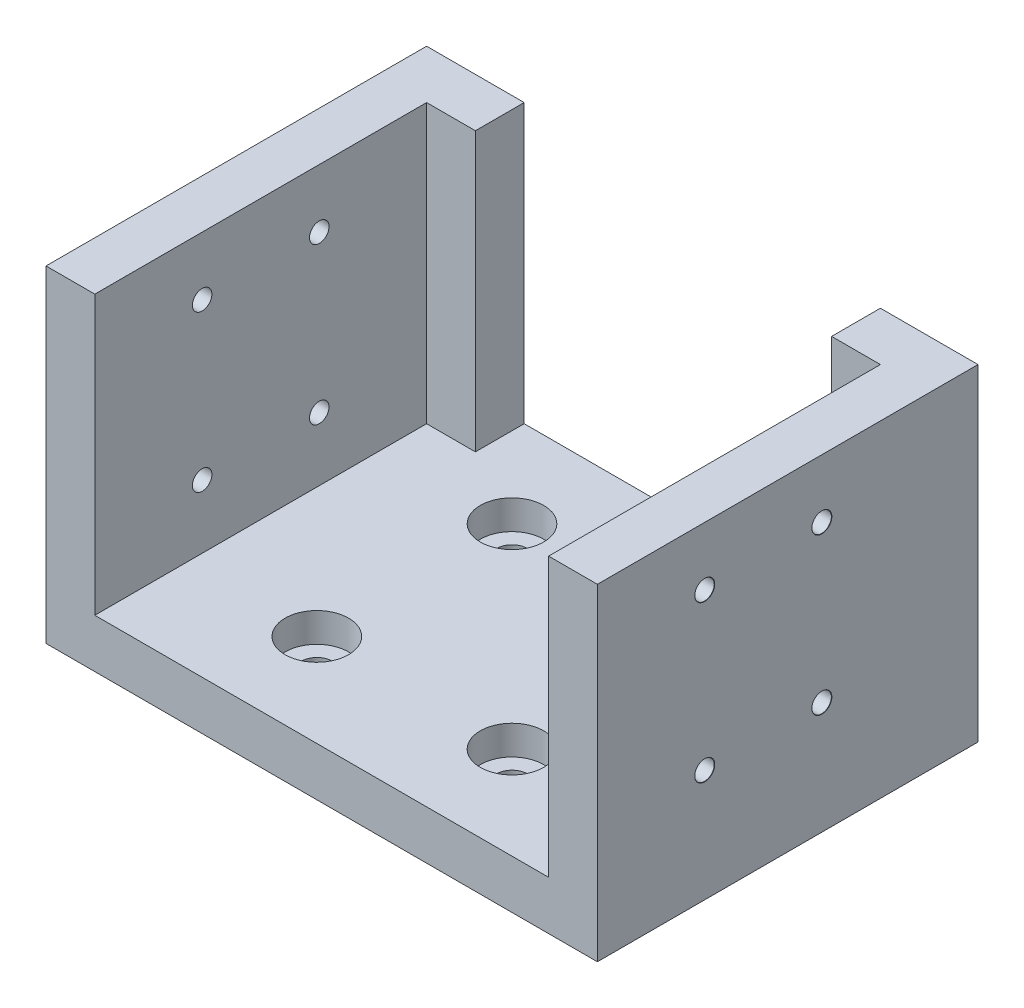
SolidWorks part; units mm, degrees
material "ABS"
ref_plane "Front Plane" through (0, 0, 0) normal (0, 0, 1) x (1, 0, 0)
ref_plane "Top Plane" through (0, 0, 0) normal (0, 1, 0) x (1, 0, 0)
ref_plane "Right Plane" through (0, 0, 0) normal (1, 0, 0) x (0, 0, -1)
sketch "Sketch9" plane through (0, 0, 0) normal (0, 1, 0) x (1, 0, 0)
  line L1 (-28.25, -19.5) -> (28.25, -19.5)
  line L2 (-28.25, -19.5) -> (-28.25, 19.5)
  line L3 (-28.25, 19.5) -> (28.25, 19.5)
  line L4 (28.25, -19.5) -> (28.25, 19.5)
  line L5 (-28.25, -19.5) -> (28.25, 19.5) construction
  line L6 (-28.25, 19.5) -> (28.25, -19.5) construction
  point P0 (0, 0)
  dimension "D1" = 56.5
  dimension "D2" = 39
extrude "Boss-Extrude7" add sketch "Sketch9" along normal blind 33.5 contours L2 L1 L4 L3
sketch "Sketch10" plane through (28.25, 0, 0) normal (1, 0, 0) x (0, 0, -1)
  line L0 (-2.5, 33.5) -> (-2.5, 0) construction
  line L2 (-19.5, 19.5) -> (19.5, 19.5) construction
  line L3 (-19.5, 33.5) -> (-19.5, 0) construction
  line L4 (19.5, 33.5) -> (19.5, 0) construction
  line L5 (-19.5, 0) -> (19.5, 0) construction
  line L6 (-19.5, 33.5) -> (19.5, 33.5) construction
  circle A0 centre (-8.5, 11.5) radius 1.05
  circle A1 centre (3.5, 11.5) radius 1.05
  circle A2 centre (3.5, 27.5) radius 1.05
  circle A3 centre (-8.5, 27.5) radius 1.05
  point P13 (-8.5, 11.5)
  point P15 (3.5, 11.5)
  point P17 (3.5, 27.5)
  point P19 (-8.5, 27.5)
  dimension "D2" = 8
  dimension "D1" = 19.5
  dimension "D3" = 22
  dimension "D4" = 6
  dimension "D5" = 6
  dimension "D6" = 16
sketch "Sketch11" plane through (0, 33.5, 0) normal (0, 1, 0) x (1, 0, 0)
  line L4 (-28.25, -19.5) -> (28.25, -19.5) construction
  line L6 (-23.25, -14.5) -> (-23.25, -19.5)
  line L7 (-23.25, -19.5) -> (23.25, -19.5)
  line L8 (23.25, 14.5) -> (-23.25, 14.5)
  line L9 (-23.25, 14.5) -> (-23.25, -14.5)
  line L10 (-23.25, -14.5) -> (23.25, -14.5)
  line L11 (23.25, -14.5) -> (23.25, 14.5)
  line L12 (23.25, 14.5) -> (-23.25, 14.5)
  line L13 (-23.25, 14.5) -> (-23.25, -14.5)
  line L15 (23.25, -14.5) -> (23.25, 14.5)
  line L16 (23.25, -14.5) -> (23.25, -19.5)
  dimension "D1" = 5
extrude "Cut-Extrude3" cut sketch "Sketch11" against normal blind 28.5
sketch "Sketch12" plane through (0, 0, -14.5) normal (0, 0, 1) x (1, 0, 0)
  line L0 (23.25, 33.5) -> (-23.25, 33.5) construction
  line L1 (-18.25, 33.5) -> (18.25, 33.5)
  line L2 (-18.25, 33.5) -> (-18.25, 5)
  line L3 (-18.25, 5) -> (18.25, 5)
  line L4 (18.25, 33.5) -> (18.25, 5)
  line L5 (-23.25, 5) -> (23.25, 5) construction
  line L6 (-23.25, 5) -> (-23.25, 33.5) construction
  line L7 (23.25, 5) -> (23.25, 33.5) construction
  dimension "D1" = 5
  dimension "D2" = 5
extrude "Cut-Extrude4" cut sketch "Sketch12" against normal through all
sketch "Sketch13" plane through (0, 5, 0) normal (0, 1, 0) x (1, 0, 0)
  line L0 (0, 0) -> (0, 21.1591) construction
  line L1 (0, 0) -> (11.6237, 0) construction
hole_wizard "CBORE for M3 Socket Head Cap Screw3" positions "3DSketch3" profile "Sketch20" counterbore size "M3" standard "IS" end condition through all
sketch3d "3DSketch3"
  line L0 (0, 5, 0) -> (0, 5, -21.1591) construction
  line L1 (0, 5, 0) -> (11.6237, 5, 0) construction
  point P0 (10, 5, -10)
  point P2 (10, 5, 10)
  point P4 (-10, 5, 10)
  point P6 (-10, 5, -10)
  dimension "D1" = 10
  dimension "D2" = 10
  dimension "D3" = 10
  dimension "D4" = 10
  dimension "D5" = 10
  dimension "D6" = 10
  dimension "D7" = 10
  dimension "D8" = 10
sketch "Sketch20" plane through (10, 5, -10) normal (1, 0, 0) x (0, 0, 1)
  line L0 (0, 0) -> (0, 5)
  line L1 (0, 5) -> (1.6, 5)
  line L3 (1.6, 5) -> (1.6, 3)
  line L4 (1.6, 3) -> (3.25, 3)
  line L5 (3.25, 3) -> (3.25, 0)
  line L7 (3.25, 0) -> (0, 0)
  line L11 (0, -6.35) -> (0, 107.95) construction
  dimension "Thru Hole Dia." = 3.2
  dimension "Thru Hole Depth" = 5
  dimension "C'Bore Dia." = 6.5
  dimension "C'Bore Depth" = 3
hole_wizard "Ø2.0mm Dowel Hole1" positions "Sketch10" profile "Sketch24" hole size "Ø2.0" standard "ANSI Metric" end condition through all
sketch "Sketch24" plane through (28.25, 27.5, 8.5) normal (0, 1, 0) x (0, 0, -1)
  line L0 (0, 0) -> (0, 56.5)
  line L1 (0, 56.5) -> (1, 56.5)
  line L2 (1, 56.5) -> (1, 0.025)
  line L3 (1, 0.025) -> (1.025, 0)
  line L5 (1.025, 0) -> (0, 0)
  line L6 (-1, 0.025) -> (-1.025, 0) construction
  line L11 (0, -6.35) -> (0, 107.95) construction
  dimension "Thru Hole Dia." = 2
  dimension "Thru Hole Depth" = 56.5
  dimension "Near C'Sink Dia." = 2.05
  dimension "Near C'Sink Angle" = 90
